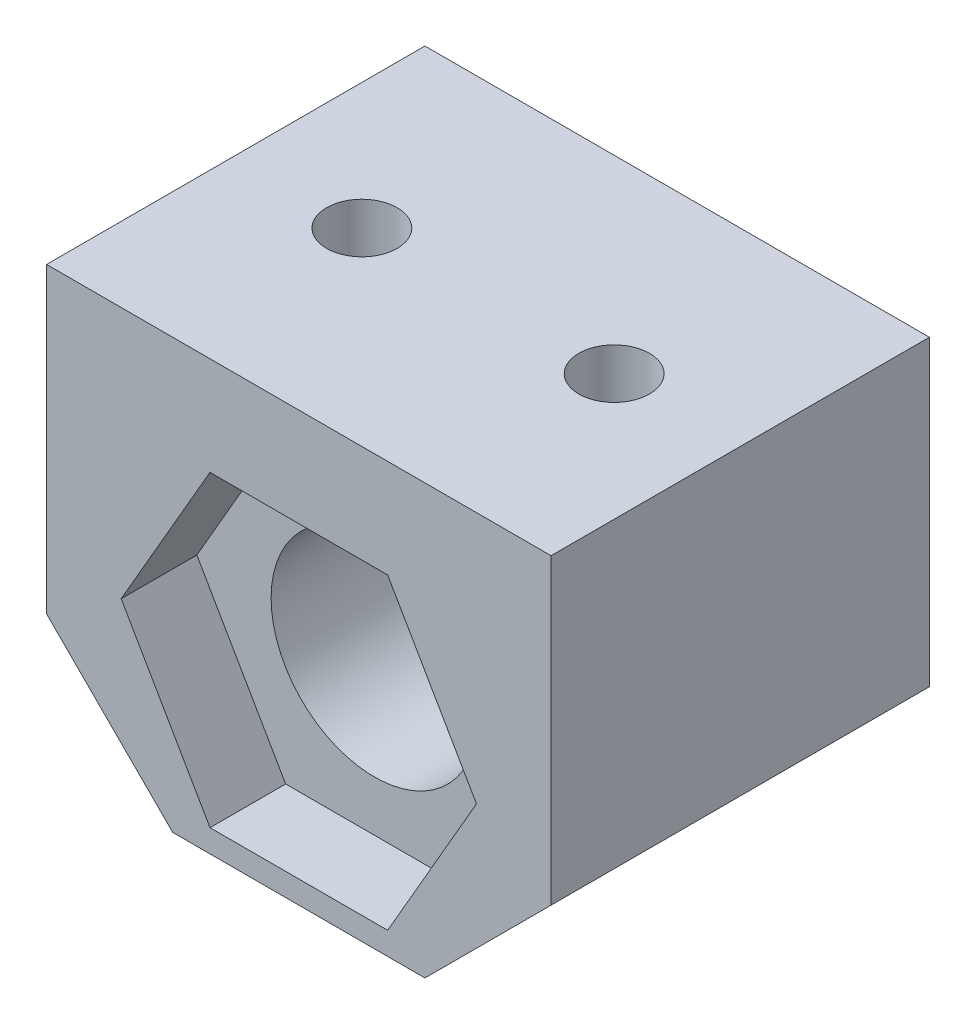
SolidWorks part; units mm, degrees
ref_plane "前视基准面" through (0, 0, 0) normal (0, 0, 1) x (1, 0, 0)
ref_plane "上视基准面" through (0, 0, 0) normal (0, 1, 0) x (1, 0, 0)
ref_plane "右视基准面" through (0, 0, 0) normal (1, 0, 0) x (0, 0, -1)
sketch "草图1" plane through (0, 0, 0) normal (0, 0, 1) x (1, 0, 0)
  line L0 (-10, 10) -> (10, 10)
  line L1 (10, 10) -> (10, -2)
  line L2 (10, -2) -> (5, -7)
  line L3 (5, -7) -> (-5, -7)
  line L4 (-5, -7) -> (-10, -2)
  line L5 (-10, -2) -> (-10, 10)
  line L6 (0, 0) -> (0, 10) construction
  line L7 (-5, 0) -> (5, 0) construction
  circle A0 centre (0, 0) radius 4.1
  point P9 (0, -7)
  dimension "D1" = 8.2
  dimension "D2" = 10
  dimension "D3" = 20
  dimension "D4" = 10
  dimension "D5" = 7
  dimension "D6" = 10
extrude "凸台-拉伸1" add sketch "草图1" along normal mid plane 15
sketch "草图2" plane through (0, 0, 7.5) normal (0, 0, 1) x (1, 0, 0)
  line L1 (7.0437, 0) -> (3.5218, 6.1)
  line L2 (3.5218, 6.1) -> (-3.5218, 6.1)
  line L3 (-3.5218, 6.1) -> (-7.0437, 0)
  line L4 (-7.0437, 0) -> (-3.5218, -6.1)
  line L5 (-3.5218, -6.1) -> (3.5218, -6.1)
  line L6 (3.5218, -6.1) -> (7.0437, 0)
  circle A0 centre (0, 0) radius 6.1 construction
  dimension "D1" = 12.2
extrude "切除-拉伸1" cut sketch "草图2" against normal blind 3
sketch "草图3" plane through (0, 10, 0) normal (0, 1, 0) x (1, 0, 0)
  line L0 (-5, 0) -> (5, 0) construction
  circle A0 centre (5, 0) radius 1.4
  circle A1 centre (-5, 0) radius 1.4
  dimension "D2" = 2.8
  dimension "D1" = 10
extrude "切除-拉伸4" cut sketch "草图3" against normal blind 10
